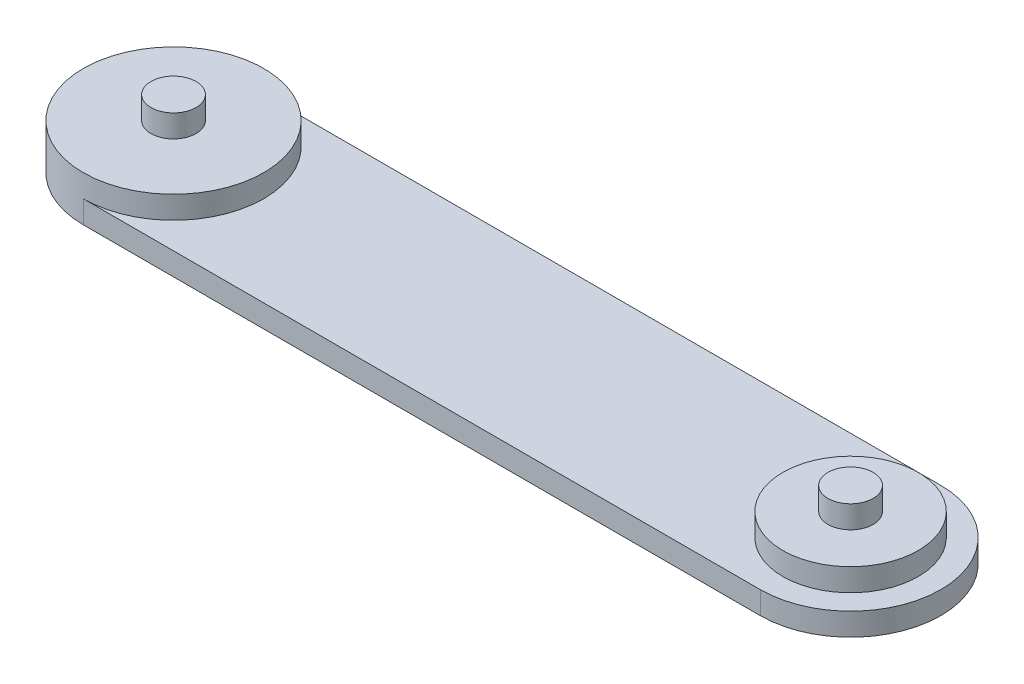
SolidWorks part; units mm, degrees
ref_plane "Front Plane" through (0, 0, 0) normal (0, 0, 1) x (1, 0, 0)
ref_plane "Top Plane" through (0, 0, 0) normal (0, 1, 0) x (1, 0, 0)
ref_plane "Right Plane" through (0, 0, 0) normal (1, 0, 0) x (0, 0, -1)
sketch "Sketch1" plane through (0, 0, 0) normal (0, 1, 0) x (1, 0, 0)
  line L1 (-300, 40) -> (0, 40)
  line L2 (-300, -40) -> (0, -40)
  arc A0 (0, -40) -> (0, 40) centre (0, 0) ccw
  arc A1 (-300, 40) -> (-300, -40) centre (-300, 0) ccw
  dimension "D1" = 80
  dimension "D2" = 80
  dimension "D3" = 300
extrude "Boss-Extrude1" add sketch "Sketch1" along normal blind 10
sketch "Sketch2" plane through (0, 10, 0) normal (0, 1, 0) x (1, 0, 0)
  circle A0 centre (-300, 0) radius 40
  circle A1 centre (0, 0) radius 30
  dimension "D1" = 80
  dimension "D2" = 60
extrude "Boss-Extrude2" add sketch "Sketch2" along normal blind 10
sketch "Sketch3" plane through (0, 20, 0) normal (0, 1, 0) x (1, 0, 0)
  circle A0 centre (0, 0) radius 10
  circle A1 centre (-300, 0) radius 10
  dimension "D1" = 20
  dimension "D2" = 20
extrude "Boss-Extrude3" add sketch "Sketch3" along normal blind 10
sketch "Sketch5" plane through (0, 0, 0) normal (0, -1, 0) x (1, 0, 0)
  line L0 (-300, 25) -> (0, 25)
  line L1 (-300, -25) -> (0, -25)
  arc A0 (0, -25) -> (0, 25) centre (0, 0) ccw
  arc A1 (-300, 25) -> (-300, -25) centre (-300, 0) ccw
  dimension "D1" = 50
  dimension "D2" = 50
extrude "Cut-Extrude1" cut sketch "Sketch5" against normal blind 2
